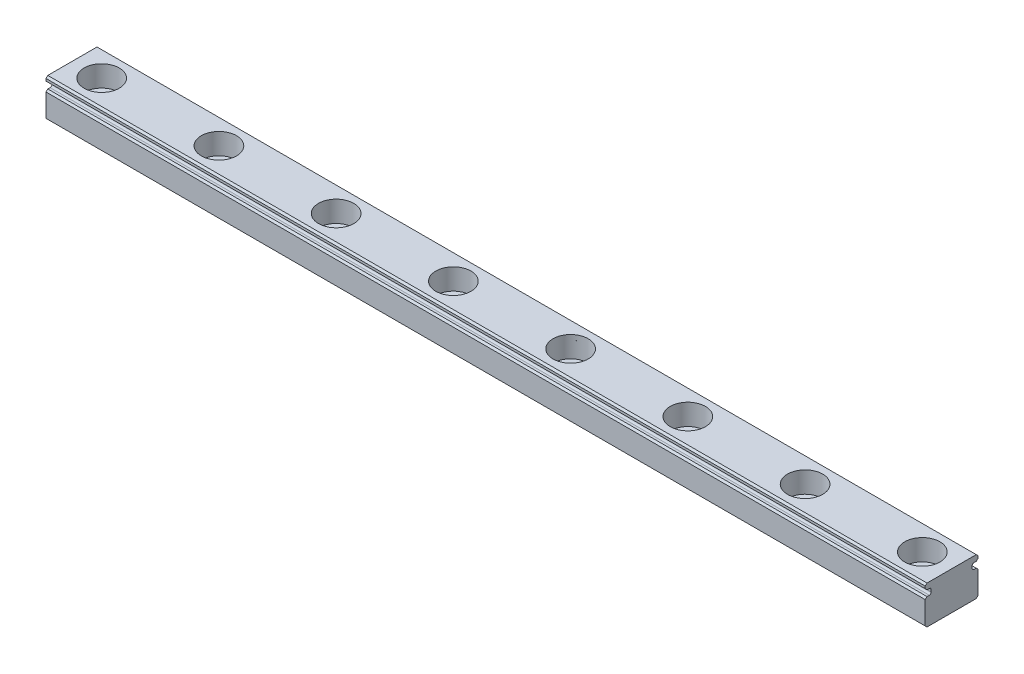
SolidWorks part; units mm, degrees
ref_plane "Front Plane" through (0, 0, 0) normal (0, 0, 1) x (1, 0, 0)
ref_plane "Top Plane" through (0, 0, 0) normal (0, 1, 0) x (1, 0, 0)
ref_plane "Right Plane" through (0, 0, 0) normal (1, 0, 0) x (0, 0, -1)
sketch "Sketch1" plane through (0, 0, 0) normal (0, 1, 0) x (1, 0, 0)
  line L1 (0, 0) -> (150, 0)
  line L2 (0, 0) -> (0, 9)
  line L3 (0, 9) -> (150, 9)
  line L4 (150, 0) -> (150, 9)
  dimension "D1" = 9
  dimension "D2" = 150
extrude "Boss-Extrude1" add sketch "Sketch1" along normal blind 6.5
sketch "Sketch2" plane through (150, 0, 0) normal (1, 0, 0) x (0, 0, -1)
  line L0 (0, 0) -> (9, 0) construction
  line L1 (0, 5.5) -> (1, 5.5)
  line L2 (0, 5.5) -> (0, 4.5)
  line L3 (0, 4.5) -> (1, 4.5)
  line L4 (1, 5.5) -> (1, 4.5)
  line L5 (9, 6.5) -> (9, 0) construction
  line L6 (9, 5.5) -> (8, 5.5)
  line L7 (9, 5.5) -> (9, 4.5)
  line L8 (9, 4.5) -> (8, 4.5)
  line L9 (8, 5.5) -> (8, 4.5)
  dimension "D1" = 5.5
  dimension "D2" = 1
  dimension "D3" = 1
  dimension "D4" = 1
  dimension "D5" = 1
extrude "Cut-Extrude1" cut sketch "Sketch2" against normal blind 156.5
sketch "Sketch3" plane through (0, 6.5, 0) normal (0, 1, 0) x (1, 0, 0)
  line L0 (0, 9) -> (0, 0) construction
  line L1 (0, 0) -> (150, 0) construction
  circle A0 centre (5, 4.5) radius 1.8
  circle A1 centre (25, 4.5) radius 1.8
  circle A2 centre (45, 4.5) radius 1.8
  circle A3 centre (65, 4.5) radius 1.8
  circle A4 centre (85, 4.5) radius 1.8
  circle A5 centre (105, 4.5) radius 1.8
  circle A6 centre (125, 4.5) radius 1.8
  circle A7 centre (145, 4.5) radius 1.8
  dimension "D1" = 5
  dimension "D2" = 4.5
  dimension "D3" = 8
extrude "Cut-Extrude2" cut sketch "Sketch3" against normal blind 9.5
sketch "Sketch4" plane through (0, 6.5, 0) normal (0, 1, 0) x (1, 0, 0)
  circle A0 centre (5, 4.5) radius 3
  circle A1 centre (25, 4.5) radius 3
  circle A2 centre (45, 4.5) radius 3
  circle A3 centre (65, 4.5) radius 3
  circle A4 centre (85, 4.5) radius 3
  circle A5 centre (105, 4.5) radius 3
  circle A6 centre (125, 4.5) radius 3
  circle A7 centre (145, 4.5) radius 3
  dimension "D1" = 8
extrude "Cut-Extrude3" cut sketch "Sketch4" against normal blind 3.6
fillet "Fillet1" radius 0.3 4 edges at (75, 5.5, -8) (75, 4.5, -8) (75, 4.5, -1) (75, 5.5, -1)
chamfer "Chamfer1" distance 0.3 angle 45 8 edges at (75, 6.5, -9) (75, 5.5, -9) (75, 4.5, -9) (75, 0, -9) (75, 0, 0) (75, 4.5, 0) (75, 5.5, 0) (75, 6.5, 0)
